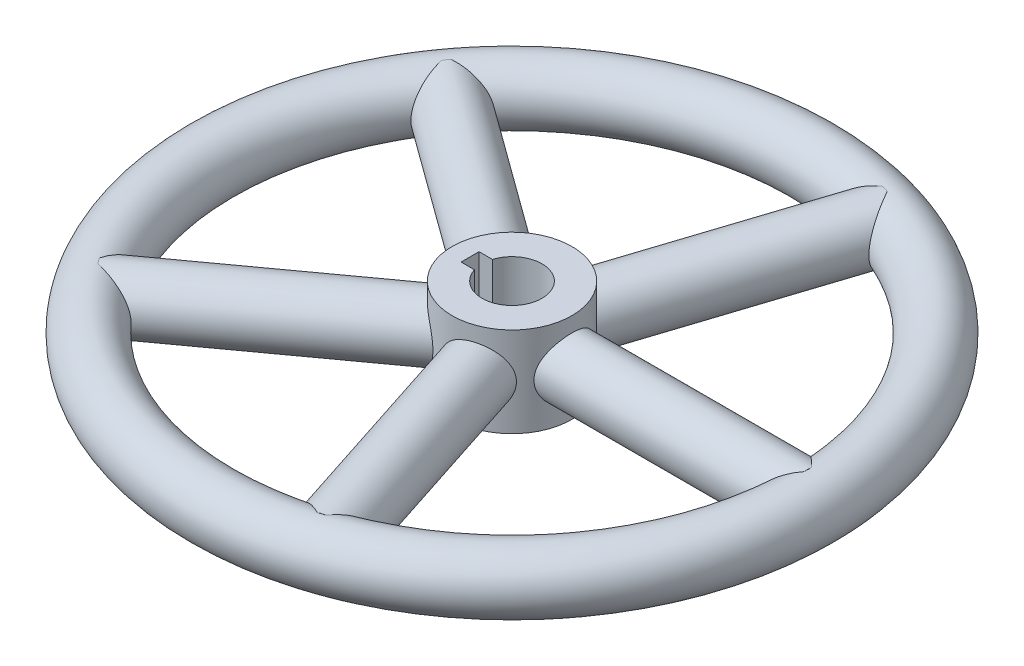
SolidWorks part; units mm, degrees
ref_plane "前视基准面" through (0, 0, 0) normal (0, 0, 1) x (1, 0, 0)
ref_plane "上视基准面" through (0, 0, 0) normal (0, 1, 0) x (1, 0, 0)
ref_plane "右视基准面" through (0, 0, 0) normal (1, 0, 0) x (0, 0, -1)
other "Configuration Table"
sketch "草图1" plane through (0, 0, 0) normal (0, 0, 1) x (1, 0, 0)
  line L0 (0, 51.9542) -> (0, -41.9221) construction
  line L1 (0, 0) -> (66.2709, 0) construction
  line L2 (5, 7.5) -> (5, -7.5)
  line L3 (5, -7.5) -> (10, -7.5)
  line L4 (10, -7.5) -> (10, 7.5)
  line L5 (10, 7.5) -> (5, 7.5)
  circle A0 centre (50, 0) radius 5
  dimension "D1" = 10
  dimension "D2" = 5
  dimension "D3" = 15
  dimension "D4" = 5
  dimension "D5" = 50
revolve "旋转1" add sketch "草图1" angle 360 about L0
sketch "草图3" plane through (0, 0, 0) normal (0, 1, 0) x (1, 0, 0)
  line L0 (-61.3044, 0) -> (68.2482, 0) construction
  line L1 (5, 0) -> (49.4006, 0)
  circle A1 centre (0, 0) radius 5 construction
  point P5 (5, 0)
  point P7 (41.9608, 0)
  point P8 (49.4006, 0)
  point P9 (45, 0)
  point P10 (10, 0)
sweep "扫描4" add path "草图3" circular profile diameter 10 parameters "D3"=10
pattern_circular "阵列(圆周)1" count 5 over 360 about axis through (0, 0, 0) along (0, 1, 0) of "扫描4"
sketch "草图2" plane through (0, 7.5, 0) normal (0, 1, 0) x (1, 0, 0)
  line L0 (-68.3474, 0) -> (59.3204, 0) construction
  line L1 (-7, 1.5) -> (-4.7697, 1.5)
  line L2 (-7, -1.5) -> (-4.7697, -1.5)
  line L3 (-7, 1.5) -> (-7, -1.5)
  circle A1 centre (0, 0) radius 5 construction
  arc A2 (-4.7697, 1.5) -> (-4.7697, -1.5) centre (0, 0) ccw
  dimension "D1" = 3
  dimension "D2" = 7
extrude "切除-拉伸1" cut sketch "草图2" against normal through all
